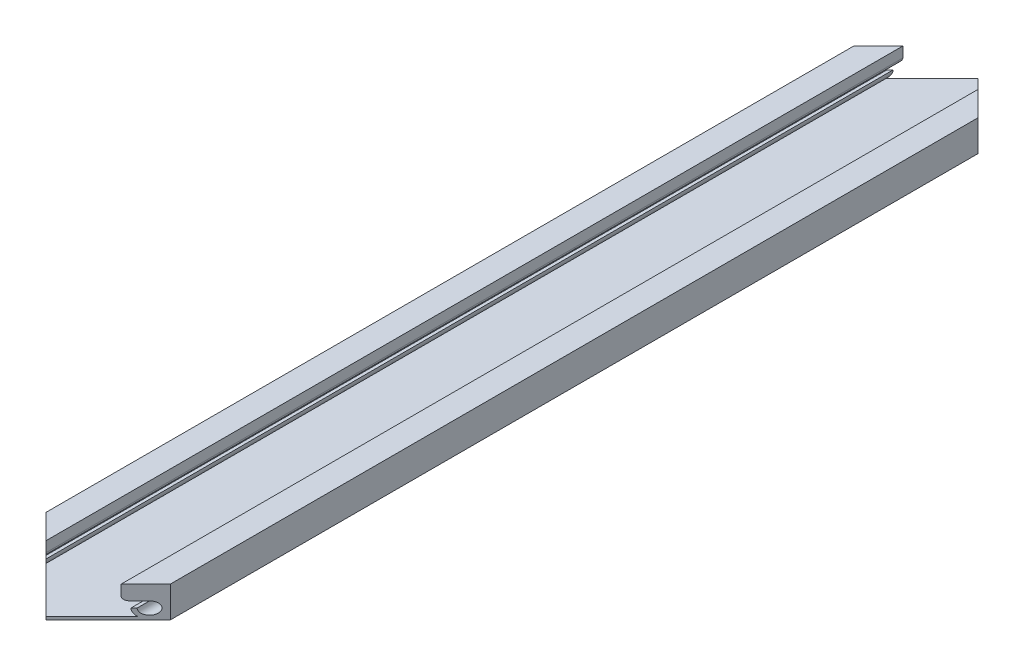
SolidWorks part; units mm, degrees
ref_plane "정면" through (0, 0, 0) normal (0, 0, 1) x (1, 0, 0)
ref_plane "윗면" through (0, 0, 0) normal (0, 1, 0) x (1, 0, 0)
ref_plane "우측면" through (0, 0, 0) normal (1, 0, 0) x (0, 0, -1)
sketch "스케치1" plane through (0, 0, 0) normal (0, 0, 1) x (1, 0, 0)
  line L1 (-30, 7.5) -> (30, 7.5)
  line L2 (-30, 7.5) -> (-30, -7.5)
  line L3 (-30, -7.5) -> (30, -7.5)
  line L4 (30, 7.5) -> (30, -7.5)
  line L5 (-30, 7.5) -> (30, -7.5) construction
  line L6 (-30, -7.5) -> (30, 7.5) construction
  point P0 (0, 0)
  dimension "D1" = 60
  dimension "D2" = 15
extrude "보스-돌출1" add sketch "스케치1" along normal blind 450
sketch "스케치2" plane through (0, 0, 0) normal (0, 0, -1) x (-1, 0, 0)
  line L0 (30, -7.5) -> (-30, -7.5) construction
  line L2 (-30, -7.5) -> (-30, 7.5) construction
  line L3 (30, 7.5) -> (30, -7.5) construction
  circle A0 centre (-25, -2.5) radius 3
  circle A1 centre (25, -2.5) radius 3
  dimension "D1" = 6
  dimension "D3" = 5
  dimension "D4" = 6
  dimension "D6" = 5
  dimension "D2" = 5
  dimension "D5" = 5
extrude "컷-돌출1" cut sketch "스케치2" against normal through all
sketch "스케치3" plane through (0, 0, 0) normal (0, 0, -1) x (-1, 0, 0)
  line L0 (-22.1716, -6) -> (22.1716, -6)
  line L1 (-20.5, -2.5) -> (-25, -2.5)
  line L2 (-25, -2.5) -> (-25, 0.5)
  line L3 (-25, 0.5) -> (25, 0.5)
  line L4 (25, 0.5) -> (25, -2.5)
  line L5 (25, -2.5) -> (20.5, -2.5)
  line L6 (30, -7.5) -> (-30, -7.5) construction
  arc A0 (22.1716, -6) -> (20.5, -2.5) centre (25, -2.5) cw
  arc A1 (-22.1716, -6) -> (-20.5, -2.5) centre (-25, -2.5) ccw
  circle A2 centre (-25, -2.5) radius 3 construction
  circle A3 centre (25, -2.5) radius 3 construction
  dimension "D2" = 1.5
  dimension "D1" = 1.5
  dimension "1.5" = 1.5
extrude "컷-돌출2" cut sketch "스케치3" against normal through all
sketch "스케치4" plane through (0, 0, 0) normal (0, 0, -1) x (-1, 0, 0)
  line L0 (-18.1431, 0.5) -> (18.1569, 0.5)
  line L1 (25, 0.5) -> (-25, 0.5) construction
  line L2 (-18.1431, 0.5) -> (-18.1431, 7.5)
  line L3 (-30, 7.5) -> (30, 7.5) construction
  line L4 (-18.1431, 7.5) -> (18.1569, 7.5)
  line L5 (18.1569, 7.5) -> (18.1569, 0.5)
  point P5 (0, 0)
  dimension "D1" = 36.3
extrude "컷-돌출3" cut sketch "스케치4" against normal through all
fillet "필렛1" radius 2 2 edges at (-18.1569, 0.5, 225) (18.1431, 0.5, 225)
sketch "스케치5" plane through (0, -7.5, 0) normal (0, -1, 0) x (1, 0, 0)
  line L0 (-30, 450) -> (-30, 420)
  line L1 (-30, 450) -> (-30, 0) construction
  line L2 (-30, 420) -> (0, 450)
  line L3 (-30, 450) -> (30, 450) construction
  line L4 (30, 450) -> (-30, 450)
  line L5 (0, 442.8165) -> (0, -66.3343) construction
  line L6 (-30, 225) -> (30, 225) construction
  line L7 (30, 450) -> (30, 0) construction
  line L8 (30, 420) -> (0, 450)
  line L9 (30, 450) -> (30, 420)
  line L10 (30, 0) -> (30, 30)
  line L11 (30, 30) -> (0, 0)
  line L12 (30, 0) -> (-30, 0)
  line L13 (-30, 30) -> (0, 0)
  line L14 (-30, 0) -> (-30, 30)
  line M8 (-30, 0) -> (30, 0)
  line M9 (30, 0) -> (30, 450)
  line M10 (30, 450) -> (-30, 450)
  line M11 (-30, 450) -> (-30, 0)
  dimension "D1" = 45
extrude "컷-돌출4" cut sketch "스케치5" against normal through all contours L8 M9 M10 | L2 M11 M10 | L13 M11 M8 | L11 M9 M8
